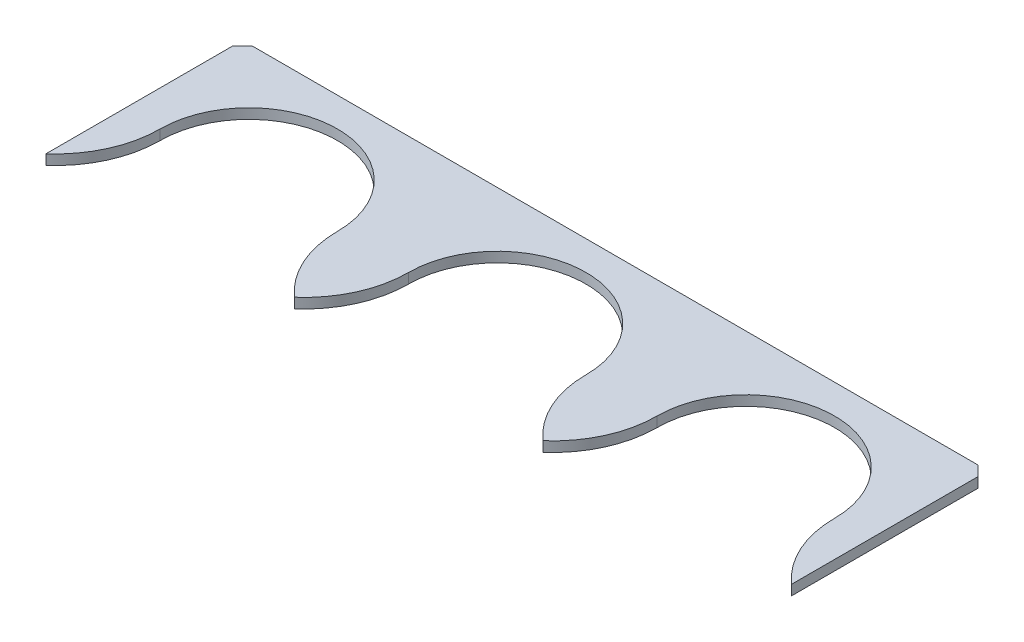
SolidWorks part; units mm, degrees
ref_plane "Front Plane" through (0, 0, 0) normal (0, 0, 1) x (1, 0, 0)
ref_plane "Top Plane" through (0, 0, 0) normal (0, 1, 0) x (1, 0, 0)
ref_plane "Right Plane" through (0, 0, 0) normal (1, 0, 0) x (0, 0, -1)
sketch "Sketch1" plane through (0, 0, 0) normal (0, 1, 0) x (1, 0, 0)
  line L0 (36.1222, -90.254) -> (36.1222, 39.921)
  line L1 (-120.4942, 39.921) -> (349.4058, 39.921)
  line L2 (-120.4942, 39.921) -> (-120.4942, -90.254)
  line L3 (-120.4942, -90.254) -> (349.4058, -90.254)
  line L4 (349.4058, 39.921) -> (349.4058, -90.254)
  line L5 (192.7386, -90.254) -> (192.7386, 39.921)
  line L6 (-120.4942, 33.571) -> (-114.1442, 39.921)
  line L7 (343.0558, 39.921) -> (349.4058, 33.571)
  circle A0 centre (-42.186, -34.374) radius 55.88
  circle A1 centre (114.4304, -34.374) radius 55.88
  circle A2 centre (271.0722, -34.374) radius 55.88
  arc A3 (-98.066, -34.374) -> (-120.4942, -83.904) centre (-163.9706, -34.374) cw
  arc A4 (13.694, -34.374) -> (36.1222, -83.904) centre (79.5987, -34.374) ccw
  arc A5 (58.5504, -34.374) -> (36.1222, -83.904) centre (-7.3542, -34.374) cw
  arc A6 (170.3104, -34.374) -> (192.7386, -83.904) centre (236.2151, -34.374) ccw
  arc A7 (215.1922, -34.374) -> (192.7386, -83.904) centre (149.3368, -34.374) cw
  arc A8 (326.9522, -34.374) -> (349.4058, -83.904) centre (392.8077, -34.374) ccw
  dimension "D3" = 111.76
  dimension "D4" = 111.76
  dimension "D5" = 111.76
  dimension "D1" = 469.9
  dimension "D2" = 130.175
  dimension "D6" = 156.6164
  dimension "D7" = 156.6164
  dimension "D8" = 78.3082
  dimension "D9" = 78.3082
  dimension "D10" = 78.3336
  dimension "D11" = 6.35
  dimension "D12" = 6.35
  dimension "D13" = 6.35
  dimension "D14" = 6.35
  dimension "D15" = 6.35
  dimension "D16" = 6.35
  dimension "D17" = 6.35
  dimension "D18" = 6.35
extrude "Boss-Extrude1" add sketch "Sketch1" against normal blind 6.35
